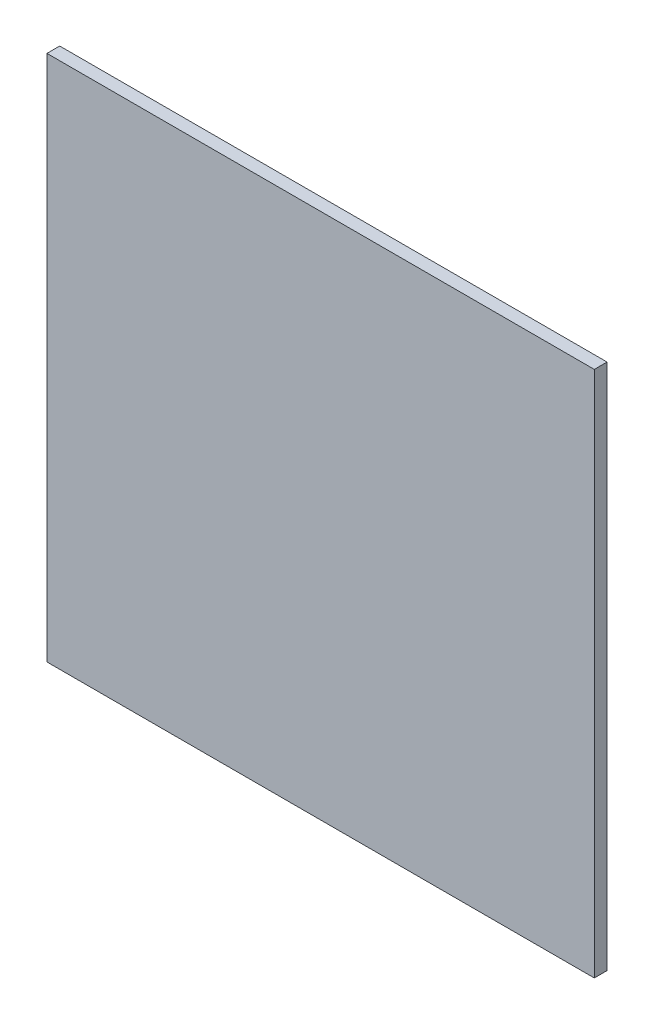
SolidWorks part; units mm, degrees
ref_plane "Front Plane" through (0, 0, 0) normal (0, 0, 1) x (1, 0, 0)
ref_plane "Top Plane" through (0, 0, 0) normal (0, 1, 0) x (1, 0, 0)
ref_plane "Right Plane" through (0, 0, 0) normal (1, 0, 0) x (0, 0, -1)
sketch "Sketch1" plane through (0, 0, 0) normal (0, 0, 1) x (1, 0, 0)
  line L1 (-34.29, -33.02) -> (34.29, -33.02)
  line L2 (-34.29, -33.02) -> (-34.29, 33.02)
  line L3 (-34.29, 33.02) -> (34.29, 33.02)
  line L4 (34.29, -33.02) -> (34.29, 33.02)
  line L5 (-34.29, -33.02) -> (34.29, 33.02) construction
  line L6 (-34.29, 33.02) -> (34.29, -33.02) construction
  point P0 (0, 0)
  dimension "D1" = 68.58
  dimension "D2" = 66.04
extrude "Boss-Extrude1" add sketch "Sketch1" along normal mid plane 1.6
